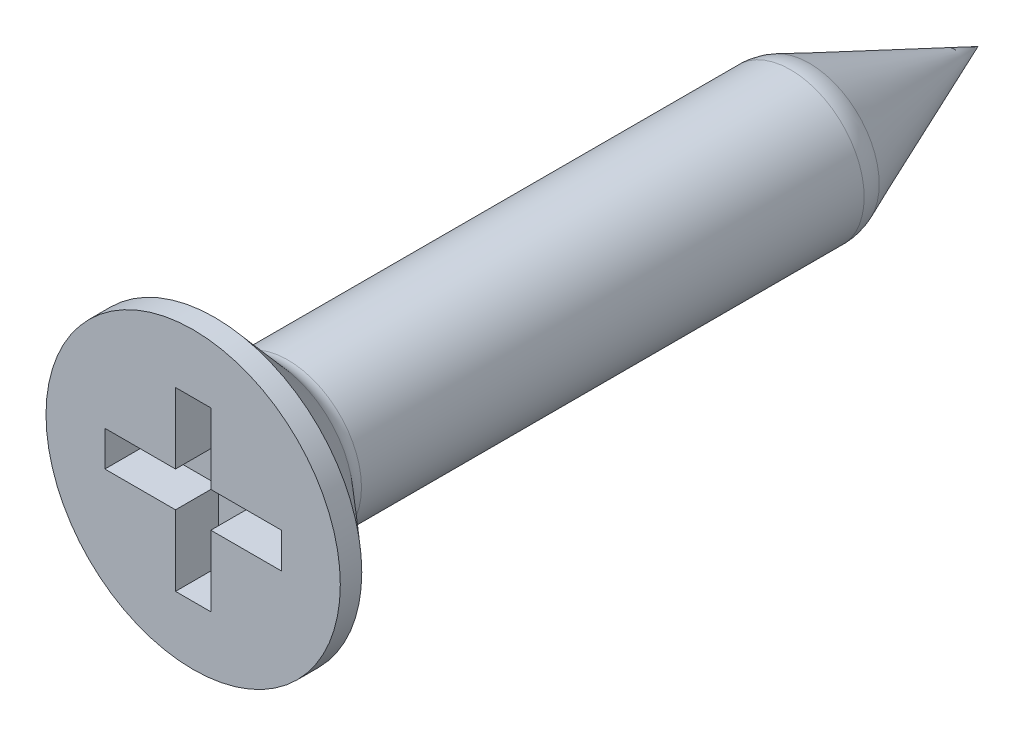
SolidWorks part; units mm, degrees
ref_plane "Front" through (0, 0, 0) normal (0, 0, 1) x (1, 0, 0)
ref_plane "Top" through (0, 0, 0) normal (0, 1, 0) x (1, 0, 0)
ref_plane "Right" through (0, 0, 0) normal (1, 0, 0) x (0, 0, -1)
sketch "Sketch1" plane through (0, 0, 0) normal (1, 0, 0) x (0, 0, -1)
  line L0 (-94.2432, 0) -> (113.0629, 0) construction
  line L1 (-1.3125, 3) -> (0, 1.5)
  line L2 (0, 1.5) -> (10.6287, 1.5)
  line L3 (10.6287, 1.5) -> (14.25, 0)
  line L4 (14.25, 0) -> (-1.75, 0)
  line L5 (-1.3125, 3) -> (-1.75, 3)
  line L6 (-1.75, 0) -> (-1.75, 3)
  dimension "D1" = 22.5
  dimension "D2" = 0.4375
  dimension "l" = 16
  dimension "k" = 1.75
  dimension "d" = 3
  dimension "dk" = 6
revolve "Revolve1" add sketch "Sketch1" angle 360 about L0
ref_plane "Plane1" through (0, 0, 0) normal (0, 0, 1) x (1, 0, 0)
sketch "Sketch5" plane through (0, 0, 1.75) normal (0, 0, 1) x (1, 0, 0)
  line L0 (-3.3742, 0) -> (3.3847, 0) construction
  line L1 (0, 3.3377) -> (0, -3.223) construction
  line L2 (0, 1.8) -> (-0.36, 1.8)
  line L3 (-0.36, 1.8) -> (-0.36, 0.36)
  line L4 (-0.36, 0.36) -> (-1.8, 0.36)
  line L5 (-1.8, 0.36) -> (-1.8, 0)
  line L6 (0.36, 1.8) -> (0, 1.8)
  line L7 (0.36, 0.36) -> (0.36, 1.8)
  line L8 (1.8, 0.36) -> (0.36, 0.36)
  line L9 (1.8, 0) -> (1.8, 0.36)
  line L10 (1.8, -0.36) -> (1.8, 0)
  line L11 (0.36, -0.36) -> (1.8, -0.36)
  line L12 (0.36, -1.8) -> (0.36, -0.36)
  line L13 (0, -1.8) -> (0.36, -1.8)
  line L14 (-0.36, -1.8) -> (0, -1.8)
  line L15 (-0.36, -0.36) -> (-0.36, -1.8)
  line L16 (-1.8, -0.36) -> (-0.36, -0.36)
  line L17 (-1.8, 0) -> (-1.8, -0.36)
  dimension "D1" = 0.36
  dimension "D2" = 0.36
  dimension "m1/2" = 1.8
  dimension "m2/2" = 1.8
extrude "Cut-Extrude1" cut sketch "Sketch5" against normal blind 0.875
fillet "Fillet1" radius 0.4 1 edges at (1.5, 0, 0)
fillet "Fillet2" radius 1 1 edges at (1.5, 0, -10.6287)
equation "\"D1@Plane1\" = \"k@Sketch1\""
equation "\"D2@Sketch1\" = \"k@Sketch1\"/4"
equation "\"D1@Sketch5\" = \"m2/2@Sketch5\"/5"
equation "\"D2@Sketch5\" = \"m1/2@Sketch5\"/5"
equation "\"D1@Cut-Extrude1\" = \"k@Sketch1\"/2"
